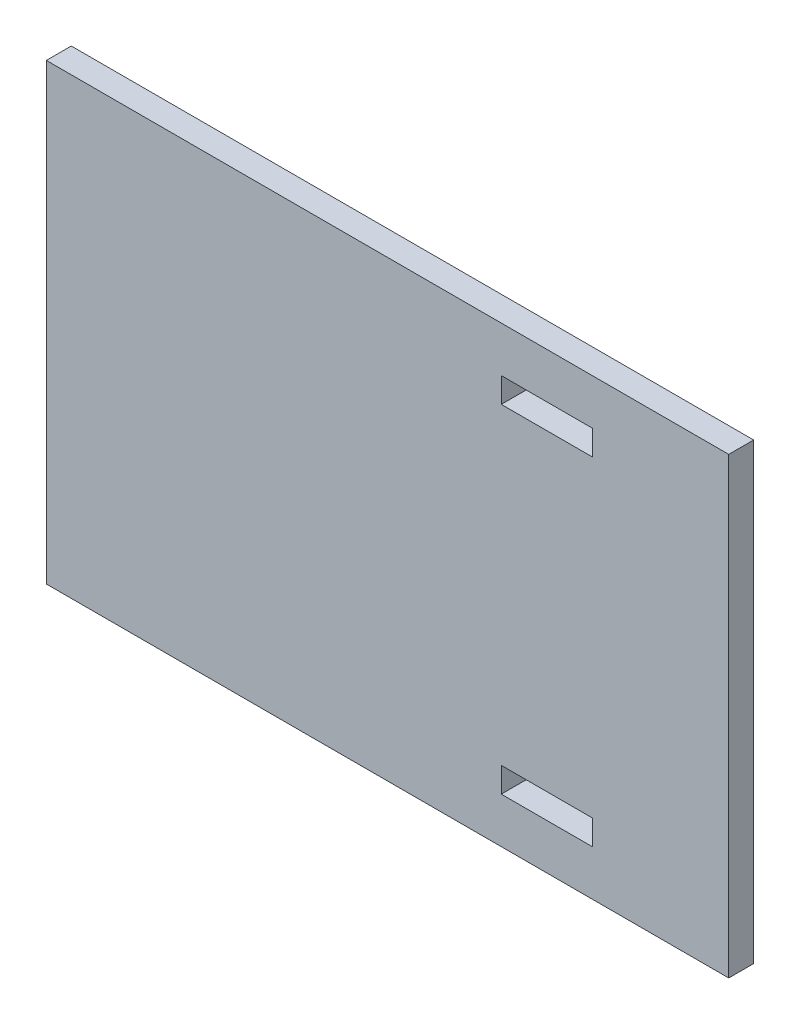
SolidWorks part; units mm, degrees
ref_plane "Front Plane" through (0, 0, 0) normal (1, 0, 0) x (0, 1, 0)
ref_plane "Top Plane" through (0, 0, 0) normal (0, 0, 1) x (0, 1, 0)
ref_plane "Right Plane" through (0, 0, 0) normal (0, 1, 0) x (-1, 0, 0)
sketch "Sketch1" plane through (0, 0, 0) normal (0, 0, 1) x (0, 1, 0)
  line L1 (0, 0) -> (49.84, 0)
  line L2 (0, 0) -> (0, 75)
  line L3 (0, 75) -> (49.84, 75)
  line L4 (49.84, 0) -> (49.84, 75)
  line L6 (42.1, 25) -> (44.84, 25)
  line L7 (42.1, 25) -> (42.1, 15)
  line L8 (42.1, 15) -> (44.84, 15)
  line L9 (44.84, 25) -> (44.84, 15)
  line L10 (42.1, 25) -> (44.84, 15) construction
  line L11 (42.1, 15) -> (44.84, 25) construction
  line L14 (5, 25) -> (7.74, 25)
  line L15 (5, 25) -> (5, 15)
  line L16 (5, 15) -> (7.74, 15)
  line L17 (7.74, 25) -> (7.74, 15)
  point P7 (43.47, 20)
  dimension "D1" = 75
  dimension "D3" = 2.74
  dimension "D4" = 10
  dimension "D6" = 39.84
  dimension "D7" = 2.74
  dimension "D2" = 5
  dimension "D8" = 5
  dimension "D5" = 20
extrude "Boss-Extrude1" add sketch "Sketch1" along normal blind 2.74
equation "\"cable width\"= .2in"
equation "\"clearance\"= 0.2mm"
equation "\"slot_width\"= \"cable width\" + \"clearance\""
equation "\"base\"= ( \"slot_width\" ) * 3 + 4 * ( 6 )"
equation "\"depth\" = 40mm"
equation "\"thick\"= 3mm"
equation "\"avg_t_wood\"= 2.74mm"
equation "\"ideal_t_wood\"= 3mm"
equation "\"kerf\"= 0.2mm"
equation "\"slot_height\"= \"avg_t_wood\" + \"kerf\""
equation "\"wood_slot_width\"= 10mm + \"kerf\""
equation "\"wood_slot_clearance\"= - .2mm"
equation "\"woodstand_width\"= 10mm"
equation "\"woodstand_length\" = 75mm"
equation "\"D1@Sketch1\"=\"woodstand_length\""
equation "\"D3@Sketch1\"=\"slot_height\"+\"wood_slot_clearance\""
equation "\"D4@Sketch1\"=\"wood_slot_width\"+\"wood_slot_clearance\""
equation "\"D1@Boss-Extrude1\"=\"avg_t_wood\""
equation "\"D7@Sketch1\"=\"avg_t_wood\""
equation "\"D5@Sketch1\"=\"depth\"*.5"
equation "\"D6@Sketch1\"=\"base\""
